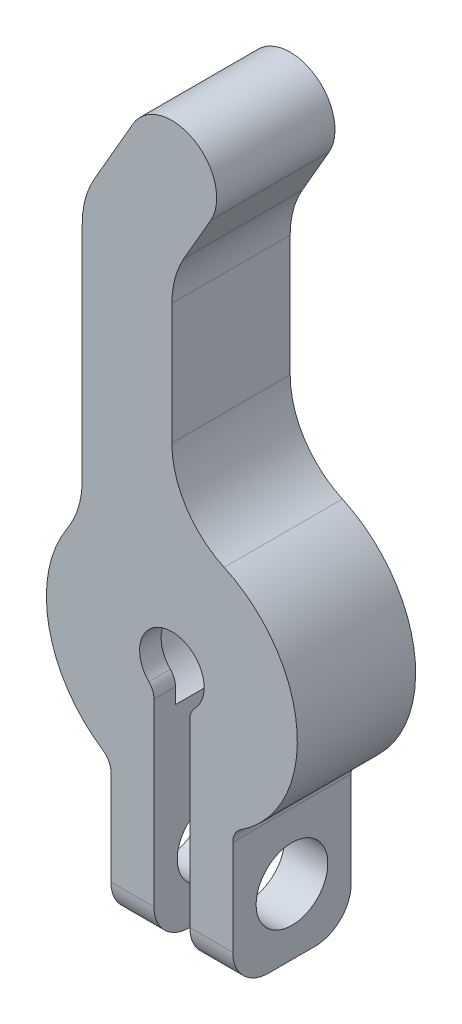
SolidWorks part; units mm, degrees
ref_plane "Front Plane" through (0, 0, 0) normal (0, 0, 1) x (1, 0, 0)
ref_plane "Top Plane" through (0, 0, 0) normal (0, 1, 0) x (1, 0, 0)
ref_plane "Right Plane" through (0, 0, 0) normal (1, 0, 0) x (0, 0, -1)
sketch "Sketch1" plane through (0, 0, 0) normal (0, 0, 1) x (1, 0, 0)
  line L0 (-1.0825, 12.625) -> (-2.5, 10.1699)
  line L1 (-2.5, 10.1699) -> (-2.5, 2.4495)
  line L2 (1.0825, 11.375) -> (0, 9.5)
  line L3 (0, 9.5) -> (0, 3.5)
  line L4 (-0.5, -1.4142) -> (-0.5, -7)
  line L5 (0.5, -1.4142) -> (0.5, -7)
  line L6 (-0.5, -7) -> (-1.7, -7)
  line L7 (-1.7, -7) -> (-1.7, -3.0594)
  line L8 (0.5, -7) -> (1.7, -7)
  line L9 (1.7, -7) -> (1.7, -3.0594)
  arc A0 (0.5, -1.4142) -> (-0.5, -1.4142) centre (0, 0) ccw
  arc A1 (-2.5, 2.4495) -> (-1.7, -3.0594) centre (0, 0) ccw
  arc A2 (1.0825, 11.375) -> (-1.0825, 12.625) centre (0, 12) ccw
  circle A3 centre (0, 0) radius 3.5 construction
  arc A5 (1.7, -3.0594) -> (0, 3.5) centre (0, 0) ccw
  circle A6 centre (0, 0) radius 1.5 construction
  point P19 (0, 0)
  dimension "D1" = 3
  dimension "D3" = 12
  dimension "D5" = 2.5
  dimension "D4" = 150
  dimension "D6" = 2.5
  dimension "D7" = 7
  dimension "D8" = 1
  dimension "D9" = 1.2
  dimension "D2" = 2
extrude "Boss-Extrude1" add sketch "Sketch1" along normal blind 2.7
sketch "Sketch2" plane through (0, 0, 2.7) normal (0, 0, 1) x (1, 0, 0)
  line L10 (0.5, -1.4142) -> (0.5, -7)
  line L11 (0.5, -7) -> (1.7, -7)
  line L12 (1.7, -7) -> (1.7, -3.0594)
  line L13 (0, 3.5) -> (0, 9.5)
  line L14 (0, 9.5) -> (1.0825, 11.375)
  line L15 (-1.0825, 12.625) -> (-2.5, 10.1699)
  line L16 (-2.5, 10.1699) -> (-2.5, 2.4495)
  line L17 (-1.7, -3.0594) -> (-1.7, -7)
  line L18 (-1.7, -7) -> (-0.5, -7)
  line L19 (-0.5, -7) -> (-0.5, -1.4142)
  line L20 (0.5, -0.7483) -> (0.5, -7)
  line L21 (0.5, -7) -> (1.7, -7)
  line L22 (1.7, -7) -> (1.7, -3.0594)
  line L23 (0, 3.5) -> (0, 9.5)
  line L24 (0, 9.5) -> (1.0825, 11.375)
  line L25 (-1.0825, 12.625) -> (-2.5, 10.1699)
  line L26 (-2.5, 10.1699) -> (-2.5, 2.4495)
  line L27 (-1.7, -3.0594) -> (-1.7, -7)
  line L28 (-1.7, -7) -> (-0.5, -7)
  line L29 (-0.5, -7) -> (-0.5, -0.7483)
  arc A0 (0.5, -0.7483) -> (-0.5, -0.7483) centre (0, 0) ccw
  arc A4 (0.5, -1.4142) -> (-0.5, -1.4142) centre (0, 0) ccw
  arc A5 (1.7, -3.0594) -> (0, 3.5) centre (0, 0) ccw
  arc A6 (1.0825, 11.375) -> (-1.0825, 12.625) centre (0, 12) ccw
  arc A7 (-2.5, 2.4495) -> (-1.7, -3.0594) centre (0, 0) ccw
  arc A9 (1.7, -3.0594) -> (0, 3.5) centre (0, 0) ccw
  arc A10 (1.0825, 11.375) -> (-1.0825, 12.625) centre (0, 12) ccw
  arc A11 (-2.5, 2.4495) -> (-1.7, -3.0594) centre (0, 0) ccw
  dimension "D2" = 1.8
  dimension "D1" = 0
extrude "Boss-Extrude2" add sketch "Sketch2" along normal blind 0.6
fillet "Fillet1" radius 0.5 2 edges at (0.5, -0.7483, 3) (-0.5, -0.7483, 3)
fillet "Fillet2" radius 2.5 4 edges at (-2.5, 10.1699, 1.65) (0, 9.5, 1.65) (-2.5, 2.4495, 1.65) (0, 3.5, 1.65)
fillet "Fillet3" radius 0.5 2 edges at (1.7, -3.0594, 1.65) (-1.7, -3.0594, 1.65)
fillet "Fillet4" radius 1 4 edges at (1.1, -7, 0) (1.1, -7, 3.3) (-1.1, -7, 0) (-1.1, -7, 3.3)
sketch "Sketch3" plane through (-1.7, 0, 0) normal (-1, 0, 0) x (0, 0, 1)
  line L0 (1.65, -7) -> (1.65, -3.3407) construction
  line L1 (2.3, -7) -> (1, -7) construction
  line L2 (3.3, -3.3407) -> (0, -3.3407) construction
  circle A0 centre (1.65, -5.1703) radius 1
  point P2 (1.65, -5.1703)
  dimension "D1" = 2
extrude "Cut-Extrude1" cut sketch "Sketch3" against normal through all
